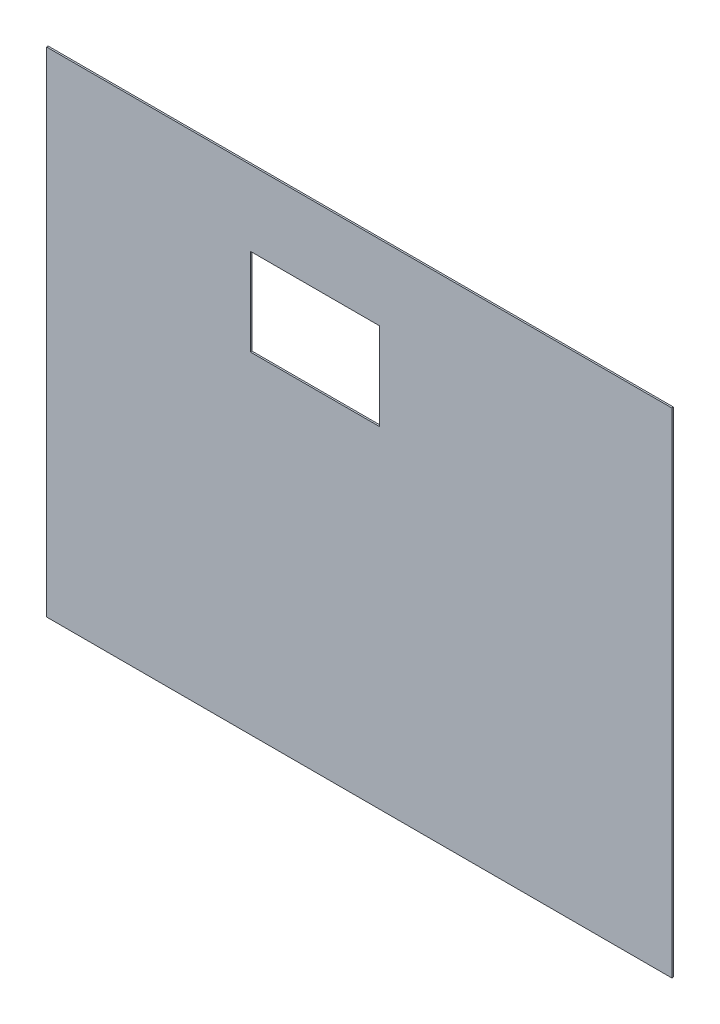
SolidWorks part; units mm, degrees
material "PBT General Purpose"
ref_plane "Alzado" through (0, 0, 0) normal (0, 0, 1) x (1, 0, 0)
ref_plane "Planta" through (0, 0, 0) normal (0, 1, 0) x (1, 0, 0)
ref_plane "Vista lateral" through (0, 0, 0) normal (1, 0, 0) x (0, 0, -1)
sketch "Croquis1" plane through (0, 0, 0) normal (0, 0, 1) x (1, 0, 0)
  line L1 (190, -150) -> (-190, -150)
  line L2 (190, -150) -> (190, 150)
  line L3 (190, 150) -> (-190, 150)
  line L4 (-190, -150) -> (-190, 150)
  line L5 (190, -150) -> (-190, 150) construction
  line L6 (190, 150) -> (-190, -150) construction
  point P0 (0, 0)
  dimension "D1" = 380
  dimension "D2" = 300
extrude "Saliente-Extruir1" add sketch "Croquis1" along normal blind 1
sketch "Croquis2" plane through (0, 0, 1) normal (0, 0, 1) x (1, 0, 0)
  line L1 (-66.1146, 104.4088) -> (12.4374, 104.4088)
  line L2 (-66.1146, 104.4088) -> (-66.1146, 51.3861)
  line L3 (-66.1146, 51.3861) -> (12.4374, 51.3861)
  line L4 (12.4374, 104.4088) -> (12.4374, 51.3861)
extrude "Cortar-Extruir1" cut sketch "Croquis2" against normal through all
